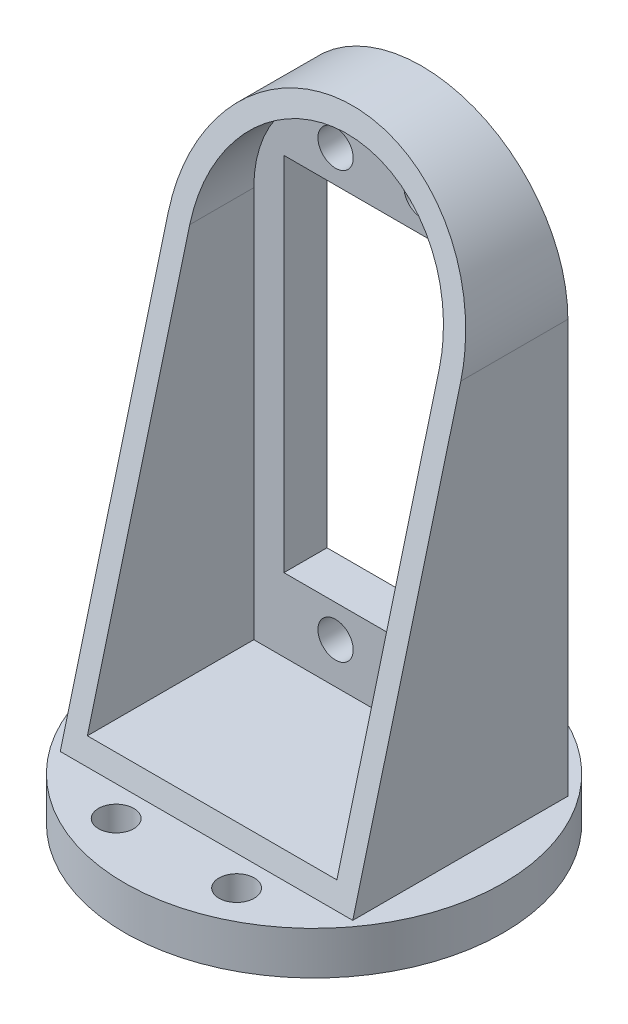
SolidWorks part; units mm, degrees
ref_plane "Front" through (0, 0, 0) normal (0, 0, 1) x (1, 0, 0)
ref_plane "Top" through (0, 0, 0) normal (0, 1, 0) x (1, 0, 0)
ref_plane "Right" through (0, 0, 0) normal (1, 0, 0) x (0, 0, -1)
sketch "Sketch1" plane through (0, 0, 0) normal (0, 0, 1) x (1, 0, 0)
  line L0 (-17, 16) -> (-17, -32)
  line L1 (-11, -21) -> (11, -21)
  line L2 (-11, -21) -> (-11, 21)
  line L3 (-11, 21) -> (11, 21)
  line L4 (11, -21) -> (11, 21)
  line L5 (-11, -21) -> (11, 21) construction
  line L6 (-11, 21) -> (11, -21) construction
  line L7 (-10, -27.25) -> (10, -27.25) construction
  line L8 (-10, -27.25) -> (-10, 27.25) construction
  line L9 (-10, 27.25) -> (10, 27.25) construction
  line L10 (10, -27.25) -> (10, 27.25) construction
  line L11 (-10, -27.25) -> (10, 27.25) construction
  line L12 (-10, 27.25) -> (10, -27.25) construction
  line L13 (17, 16) -> (17, -32)
  line L14 (17, -32) -> (-17, -32)
  circle A0 centre (0, 16) radius 17
  circle A1 centre (-5, 24.75) radius 2.05
  circle A2 centre (5, 24.75) radius 2.05
  circle A3 centre (-5, -24.75) radius 2.05
  circle A4 centre (5, -24.75) radius 2.05
  circle A5 centre (0, 10) radius 6
  point P0 (0, 0)
  point P5 (0, 0)
  point P27 (0, 0)
  dimension "D5" = 34
  dimension "D8" = 4.1
  dimension "D9" = 4.1
  dimension "D15" = 12
  dimension "D1" = 42
  dimension "D2" = 22
  dimension "D3" = 54.5
  dimension "D4" = 20
  dimension "D6" = 16
  dimension "D7" = 32
  dimension "D10" = 5
  dimension "D11" = 10
  dimension "D12" = 3.75
  dimension "D14" = 49.5
  dimension "D16" = 10
  dimension "D13" = 2
extrude "Boss-Extrude1" add sketch "Sketch1" along normal blind 5 contours A0 L8 L9 L10 | L8 A0 L10 L9 A5 A2 A1 | A0 L0 L14 L13 L10 L7 L8 | A0 L8 L7 L10 A4 A3 | L2 L1 L4 L3
sketch "Sketch2" plane through (0, 0, 5) normal (0, 0, 1) x (1, 0, 0)
  line L0 (-14.5, 16) -> (-14.5, -29.5)
  line L1 (-14.5, -29.5) -> (14.5, -29.5)
  line L2 (14.5, -29.5) -> (14.5, 16)
  line L3 (17, -32) -> (17, 16)
  line L4 (-17, 16) -> (-17, -32)
  line L5 (-17, -32) -> (17, -32)
  line L6 (17, -32) -> (17, 16)
  line L7 (-17, 16) -> (-17, -32)
  line L8 (-17, -32) -> (17, -32)
  arc A0 (14.5, 16) -> (-14.5, 16) centre (0, 16) ccw
  arc A1 (17, 16) -> (-17, 16) centre (0, 16) ccw
  arc A2 (17, 16) -> (-17, 16) centre (0, 16) ccw
  dimension "D1" = 0
  dimension "D2" = 2.5
extrude "Boss-Extrude2" add sketch "Sketch2" along normal blind 20
sketch "Sketch3" plane through (17, 0, 0) normal (1, 0, 0) x (0, 0, -1)
  line L0 (-25, -32) -> (-8, 33)
  line L1 (0, 33) -> (-25, 33) construction
  line L2 (-8, 33) -> (-25, 33)
  line L3 (-25, 33) -> (-25, -32)
  line L4 (0, 16) -> (0, 33) construction
  dimension "D1" = 8
extrude "Cut-Extrude1" cut sketch "Sketch3" against normal through all
sketch "Sketch4" plane through (0, -32, 0) normal (0, -1, 0) x (1, 0, 0)
  line L0 (0, 0) -> (0, 25) construction
  line L1 (-17, 25) -> (17, 25) construction
  circle A0 centre (0, 12.5) radius 22
  dimension "D1" = 44
extrude "Boss-Extrude3" add sketch "Sketch4" along normal blind 5
sketch "Sketch5" plane through (0, -32, 0) normal (0, 1, 0) x (1, 0, 0)
  circle A0 centre (0, 5) radius 2.05
  circle A1 centre (0, -12.5) radius 22 construction
  circle A2 centre (-7, -28.5) radius 2.05
  circle A3 centre (7, -28.5) radius 2.05
  dimension "D1" = 4.1
  dimension "D3" = 4.1
  dimension "D4" = 4.1
  dimension "D2" = 17.5
  dimension "D5" = 7
  dimension "D6" = 7
  dimension "D7" = 16
extrude "Cut-Extrude2" cut sketch "Sketch5" against normal blind 5
